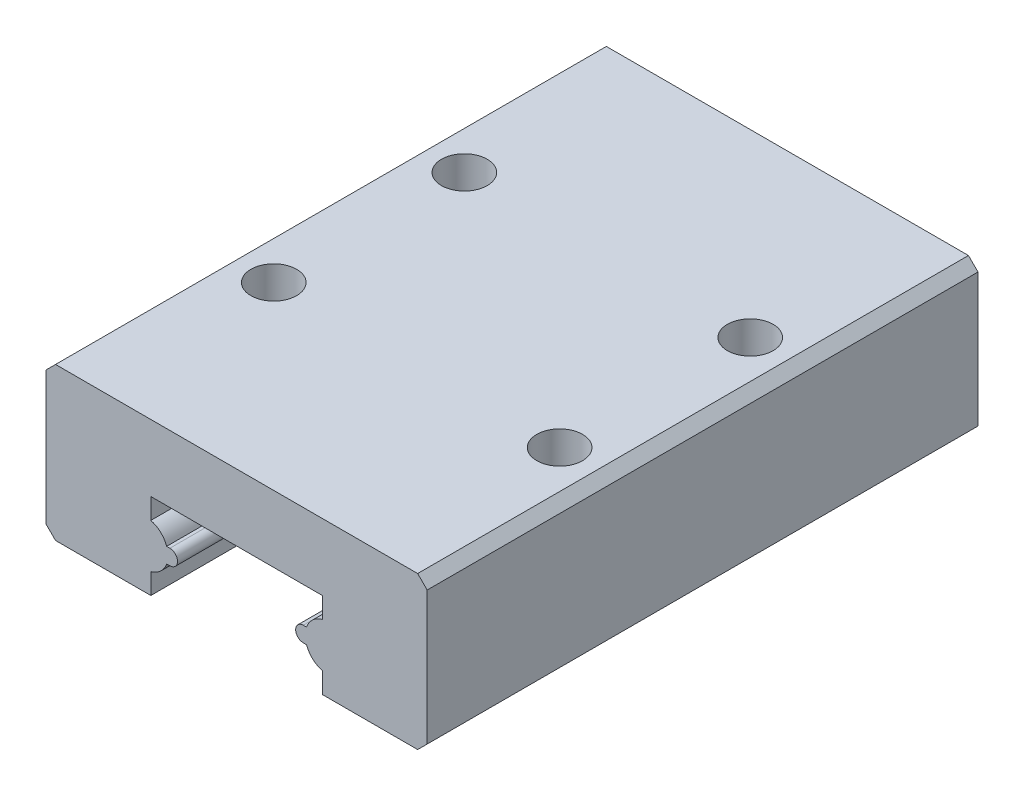
SolidWorks part; units mm, degrees
ref_plane "前视基准面" through (0, 0, 0) normal (0, 0, 1) x (1, 0, 0)
ref_plane "上视基准面" through (0, 0, 0) normal (0, 1, 0) x (1, 0, 0)
ref_plane "右视基准面" through (0, 0, 0) normal (1, 0, 0) x (0, 0, -1)
sketch "草图1" plane through (0, 0, 0) normal (0, 0, 1) x (1, 0, 0)
  line L0 (10, 4.5) -> (10, 8) construction
  line L2 (0, 0.5) -> (0, 7.5)
  line L3 (0.5, 8) -> (19.5, 8)
  line L4 (20, 0.5) -> (20, 7.5)
  line L6 (5.5, 1.0881) -> (5.5, 2.25) construction
  line L7 (5.5, 4.5) -> (14.5, 4.5)
  line L8 (14.5, 3.4119) -> (14.5, 4.5)
  line L9 (6.5, 4.5) -> (6.5, 2.25) construction
  line L10 (5.5, 2.25) -> (5.2, 2.25) construction
  line L11 (6.5, 2.65) -> (6.3314, 2.65)
  line L12 (6.5, 1.85) -> (6.3314, 1.85)
  line L13 (5.5, 3.4119) -> (5.5, 4.5)
  line L14 (13.5, 1.85) -> (13.6686, 1.85)
  line L15 (13.5, 2.65) -> (13.6686, 2.65)
  line L17 (0, 7.5) -> (0.5, 8)
  line L18 (19.5, 8) -> (20, 7.5)
  line L19 (19.5, 0) -> (20, 0.5)
  line L20 (0, 0.5) -> (0.5, 0)
  line L21 (0.5, 0) -> (5.5, 0)
  line L22 (19.5, 0) -> (14.5, 0)
  line L23 (14.5, 0) -> (14.5, 1.0881)
  line L24 (5.5, 1.0881) -> (5.5, 0)
  arc A0 (6.3423, 2.6176) -> (6.3423, 1.8824) centre (6.5, 2.25) ccw construction
  arc A1 (5.5, 1.0881) -> (6.3314, 1.85) centre (5.2, 2.25) ccw
  arc A2 (6.3314, 2.65) -> (5.5, 3.4119) centre (5.2, 2.25) ccw
  arc A3 (6.5, 1.85) -> (6.5, 2.65) centre (6.5, 2.25) ccw
  arc A4 (6.3423, 1.8824) -> (6.3423, 2.6176) centre (5.2, 2.25) ccw construction
  arc A5 (14.5, 1.0881) -> (13.6686, 1.85) centre (14.8, 2.25) cw
  arc A6 (13.5, 1.85) -> (13.5, 2.65) centre (13.5, 2.25) cw
  arc A7 (13.6686, 2.65) -> (14.5, 3.4119) centre (14.8, 2.25) cw
  point P0 (0, 0)
  point P1 (20, 8)
  point P2 (0, 8)
  point P3 (20, 0)
  dimension "D7" = 0.8
  dimension "D9" = 2.4
  dimension "D1" = 8
  dimension "D2" = 20
  dimension "D3" = 3.5
  dimension "D4" = 9
  dimension "D5" = 1
  dimension "D6" = 2.25
  dimension "D8" = 0.3
extrude "凸台-拉伸1" add sketch "草图1" along normal blind 28.9
sketch "草图2" plane through (0, 8, 0) normal (0, 1, 0) x (1, 0, 0)
  line L0 (10, -19.45) -> (10, -28.9) construction
  line L1 (2.5, -19.45) -> (17.5, -19.45) construction
  line L2 (2.5, -19.45) -> (2.5, -9.45) construction
  line L3 (2.5, -9.45) -> (17.5, -9.45) construction
  line L4 (17.5, -19.45) -> (17.5, -9.45) construction
  line L5 (19.5, -28.9) -> (0.5, -28.9) construction
  line L6 (2.5, -14.45) -> (0.5, -14.45) construction
  line L7 (0.5, -28.9) -> (0.5, 0) construction
  circle A0 centre (2.5, -19.45) radius 1.2
  circle A1 centre (2.5, -9.45) radius 1.2
  circle A2 centre (17.5, -9.45) radius 1.2
  circle A3 centre (17.5, -19.45) radius 1.2
  dimension "D3" = 2.4
  dimension "D1" = 10
  dimension "D2" = 15
extrude "切除-拉伸1" cut sketch "草图2" against normal blind 5
